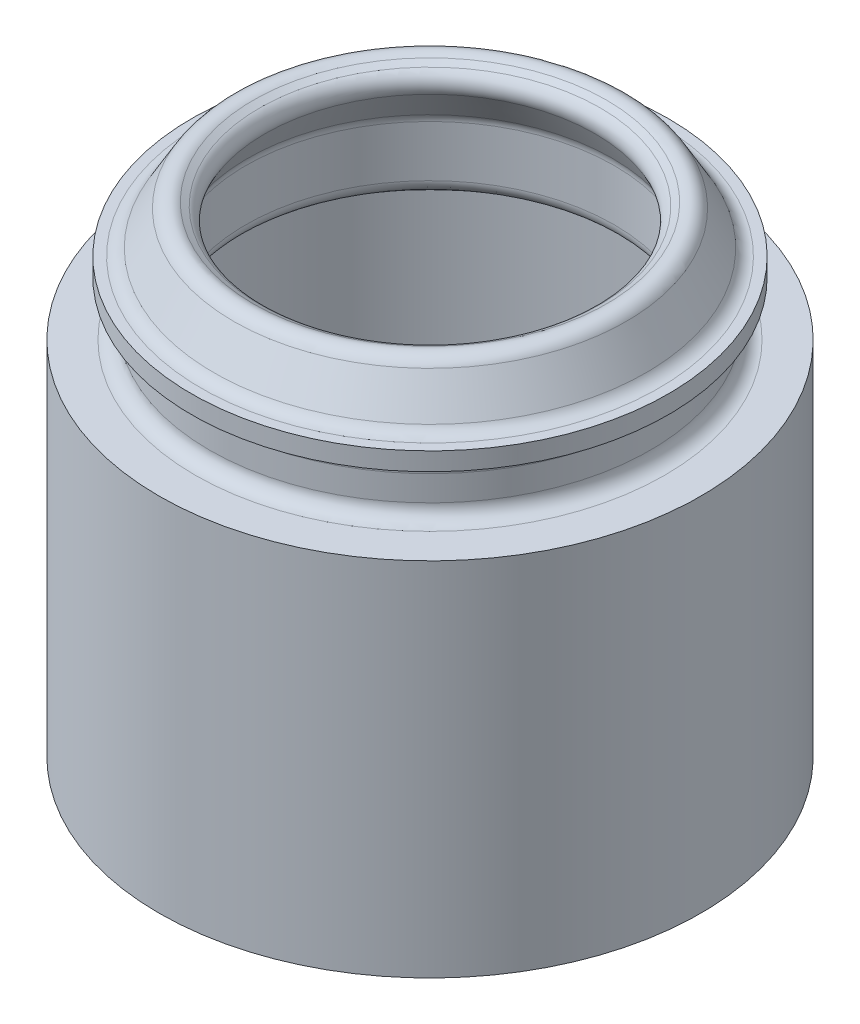
SolidWorks part; units mm, degrees
ref_plane "Front Plane" through (0, 0, 0) normal (0, 0, 1) x (1, 0, 0)
ref_plane "Top Plane" through (0, 0, 0) normal (0, 1, 0) x (1, 0, 0)
ref_plane "Right Plane" through (0, 0, 0) normal (1, 0, 0) x (0, 0, -1)
sketch "Sketch1" plane through (0, 0, 0) normal (0, 1, 0) x (1, 0, 0)
  circle A0 centre (0, 0) radius 7.5
  dimension "D1" = 15
extrude "Boss-Extrude1" add sketch "Sketch1" along normal blind 10
sketch "Sketch2" plane through (0, 10, 0) normal (0, 1, 0) x (1, 0, 0)
  circle A0 centre (0, 0) radius 6.5
  circle A1 centre (0, 0) radius 7.5
  circle A2 centre (0, 0) radius 7.5
  dimension "D1" = 0
  dimension "D2" = 1
extrude "Cut-Extrude1" cut sketch "Sketch2" against normal blind 8.5 contours A0
ref_axis "Axis1" through (0, 1.5, 0) along (0, 1, 0)
sketch "Sketch3" plane through (0, 0, 0) normal (0, 0, 1) x (1, 0, 0)
  line L0 (-7, 10) -> (-6.5, 10)
  line L1 (7.5, 10) -> (-7.5, 10) construction
  line L2 (-6.1, 10.4) -> (-6.1, 11.1)
  line L3 (-6.5, 11.5) -> (-6.6, 11.5)
  line L4 (-6.6, 11.5) -> (-6.6, 12)
  line L5 (-6.6, 12) -> (-6.3309, 12)
  line L6 (-5.9845, 12.2) -> (-5.434, 13.1536)
  line L7 (-4.8876, 13.3) -> (-4.7144, 13.2)
  line L8 (-6.5, 10) -> (-6.5, 1.5) construction
  line L9 (-4.5679, 12.6536) -> (-5.0464, 11.8249)
  line L10 (-5.1, 11.6249) -> (-5.1, 10.2058)
  line L11 (-5.2675, 9.8804) -> (-6.5, 9)
  line L12 (-6.5, 9) -> (-7, 9)
  line L13 (-7, 9) -> (-7, 10)
  line L14 (-7.5, 10) -> (-6.5, 10) construction
  line L15 (6.5, 10) -> (-6.5, 10) construction
  arc A0 (-6.3309, 12) -> (-5.9845, 12.2) centre (-6.3309, 12.4) ccw
  arc A1 (-6.1, 11.1) -> (-6.5, 11.5) centre (-6.5, 11.1) ccw
  arc A2 (-6.5, 10) -> (-6.1, 10.4) centre (-6.5, 10.4) ccw
  arc A3 (-5.1, 10.2058) -> (-5.2675, 9.8804) centre (-5.5, 10.2058) cw
  arc A4 (-5.0464, 11.8249) -> (-5.1, 11.6249) centre (-4.7, 11.6249) ccw
  arc A5 (-5.434, 13.1536) -> (-4.8876, 13.3) centre (-5.0876, 12.9536) cw
  arc A6 (-4.7144, 13.2) -> (-4.5679, 12.6536) centre (-4.9144, 12.8536) cw
  point P19 (-7, 10)
  point P20 (0, 0)
  point P21 (-5.1, 10)
  point P24 (-5.1, 10)
  point P25 (-6.5, 10)
  point P29 (-6.1, 12)
  point P32 (-6.1, 11.5)
  point P35 (-6.1, 10)
  point P38 (-5.1, 10)
  point P43 (-5.234, 13.5)
  point P46 (-4.3679, 13)
  dimension "D10" = 0.4
  dimension "D1" = 1.5
  dimension "D2" = 0.1
  dimension "D3" = 0.5
  dimension "D4" = 0.5
  dimension "D5" = 1
  dimension "D6" = 60
  dimension "D7" = 1
  dimension "D8" = 1
  dimension "D9" = 3.5
revolve "Revolve1" add sketch "Sketch3" angle 360 about axis through (0, 1.5, 0) along (0, 1, 0)
